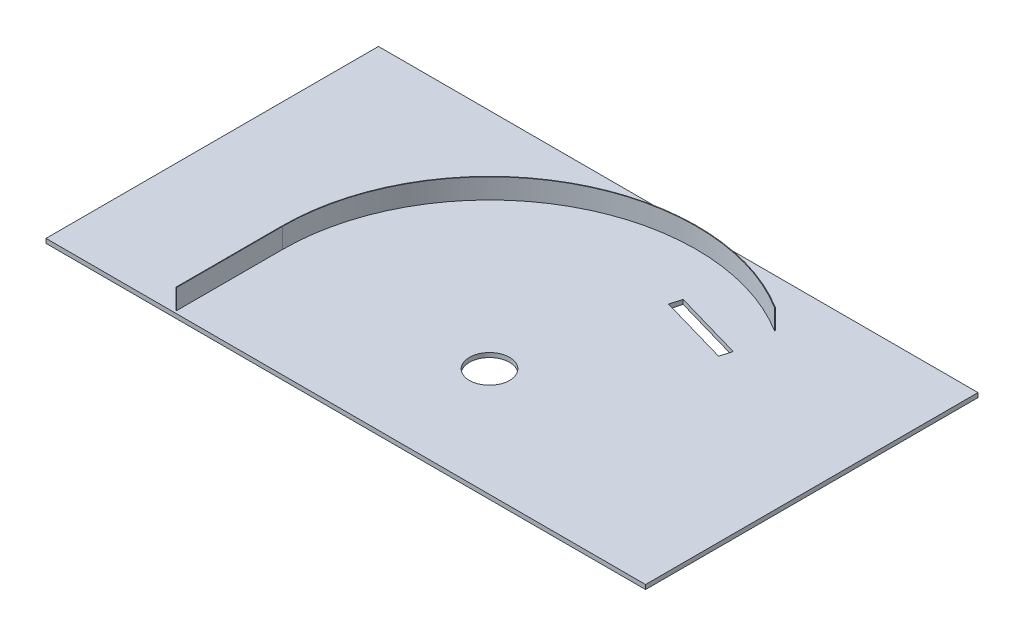
SolidWorks part; units mm, degrees
material "Particle Board"
ref_plane "Front Plane" through (0, 0, 0) normal (0, 0, 1) x (1, 0, 0)
ref_plane "Top Plane" through (0, 0, 0) normal (0, 1, 0) x (1, 0, 0)
ref_plane "Right Plane" through (0, 0, 0) normal (1, 0, 0) x (0, 0, -1)
sketch "Sketch3" plane through (0, 0, 0) normal (0, 1, 0) x (1, 0, 0)
  line L1 (0, 0) -> (-839.8654, 0) construction
  line L2 (0, 0) -> (-451.1992, 260.5) construction
  line L5 (-524, 0) -> (-525.5875, 0)
  line L6 (277.6777, 444.3772) -> (277.6777, 446.248)
  circle A0 centre (0, 0) radius 254 construction
  arc A3 (277.6777, 444.3772) -> (-524, 0) centre (0, 0) ccw
  arc A4 (277.6777, 446.248) -> (-525.5875, 0) centre (0, 0) ccw
  arc A5 (278.5189, 445.7235) -> (-525.5875, 0) centre (0, 0) ccw construction
  dimension "D1" = 524
  dimension "D2" = 1.5875
  dimension "D4" = 122
  dimension "D5" = 508
  dimension "D3" = 30
extrude "Boss-Extrude1" add sketch "Sketch3" along normal blind 50.8
sketch "Sketch4" plane through (0, 0, 0) normal (0, 1, 0) x (1, 0, 0)
  line L5 (-848, 566.7) -> (670.6777, 566.7)
  line L6 (-848, 566.7) -> (-848, -275.4)
  line L7 (-848, -275.4) -> (670.6777, -275.4)
  line L8 (670.6777, 566.7) -> (670.6777, -275.4)
  dimension "D1" = 275.4
  dimension "D2" = 848
  dimension "D3" = 566.7
  dimension "D4" = 393
extrude "Boss-Extrude2" add sketch "Sketch4" against normal blind 11.1125
hole_wizard "Ø20.0mm Dowel Hole1" positions "Sketch6" profile "Sketch7" hole size "Ø20.0" standard "ANSI Metric" end condition through all
sketch "Sketch6" plane through (0, 0, 0) normal (0, 1, 0) x (1, 0, 0)
  point P0 (0, 0)
sketch "Sketch7" plane through (0, 0, 0) normal (1, 0, 0) x (0, 0, 1)
  line L0 (0, 0) -> (0, 11.1125)
  line L1 (0, 11.1125) -> (50.8, 11.1125)
  line L2 (50.8, 11.1125) -> (50.8, 0)
  line L5 (50.8, 0) -> (0, 0)
  line L11 (0, -6.35) -> (0, 107.95) construction
  dimension "Thru Hole Dia." = 101.6
  dimension "Thru Hole Depth" = 11.1125
ref_plane "Plane1" through (0, 0, 269.05) normal (0, 0, 1) x (1, 0, 0)
sketch "Sketch8" plane through (0, 0, 0) normal (0, 0, 1) x (1, 0, 0)
  line L1 (-525.5875, 50.8) -> (-524, 50.8)
  line L2 (-525.5875, 50.8) -> (-525.5875, 0)
  line L3 (-525.5875, 0) -> (-524, 0)
  line L4 (-524, 50.8) -> (-524, 0)
extrude "Boss-Extrude3" add sketch "Sketch8" along normal up to surface (269.05 mm away) up to plane "Plane1"
sketch "Sketch9" plane through (0, 0, 0) normal (0, 1, 0) x (1, 0, 0)
  line L0 (270.6691, 346.7379) -> (92.8357, 397.7308)
  line L1 (92.8357, 397.7308) -> (84.5666, 368.8929)
  line L2 (84.5666, 368.8929) -> (262.4, 317.9)
  line L3 (262.4, 317.9) -> (270.6691, 346.7379)
  line L6 (0, 0) -> (670.6777, 0) construction
  line L7 (670.6777, -275.4) -> (670.6777, 566.7) construction
  dimension "D1" = 185
  dimension "D2" = 30
  dimension "D3" = 16
  dimension "D4" = 262.4
  dimension "D5" = 317.9
extrude "Cut-Extrude1" cut sketch "Sketch9" against normal through all
sketch "Sketch10" plane through (0, 0, 0) normal (0, 1, 0) x (1, 0, 0)
  line L0 (0, 0) -> (-545.6, 0) construction
  line L1 (0, 0) -> (277.6777, 444.3772) construction
  line L2 (0, 0) -> (195.5256, 509.3615) construction
  line L3 (0, 0) -> (94.7424, 537.3111) construction
  circle A0 centre (0, 0) radius 545.6 construction
  dimension "D1" = 11
  dimension "D2" = 11
